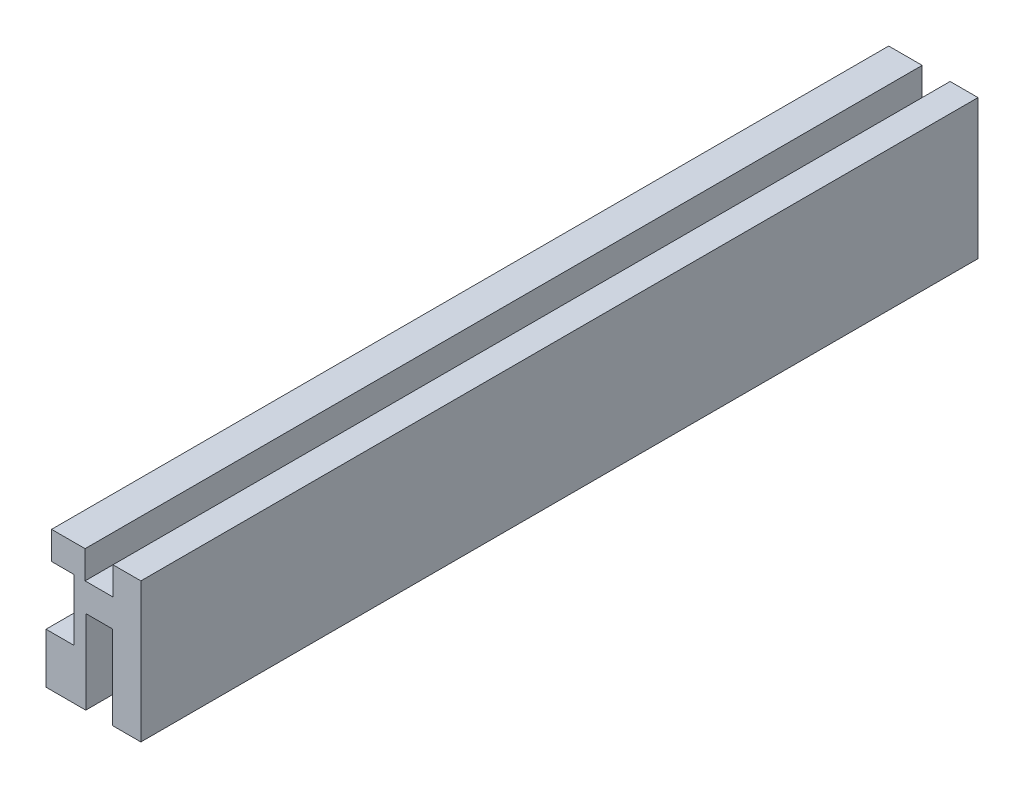
SolidWorks part; units mm, degrees
material "ABS"
ref_plane "Front Plane" through (0, 0, 0) normal (0, 0, 1) x (1, 0, 0)
ref_plane "Top Plane" through (0, 0, 0) normal (0, 1, 0) x (1, 0, 0)
ref_plane "Right Plane" through (0, 0, 0) normal (1, 0, 0) x (0, 0, -1)
sketch "Sketch1" plane through (0, 0, 0) normal (0, 0, 1) x (1, 0, 0)
  line L0 (0, 25) -> (0, -25) construction
  line L1 (15, 25) -> (5, 25)
  line L2 (-17, 25) -> (-17, 15)
  line L3 (-17, 15) -> (-9, 15)
  line L4 (-9, 15) -> (-9, -7)
  line L5 (-9, -7) -> (-19, -7)
  line L6 (-19, -7) -> (-19, -25)
  line L7 (-19, -25) -> (-4.75, -25)
  line L8 (-4.75, -25) -> (-4.75, 5)
  line L9 (-4.75, 5) -> (4.75, 5)
  line L10 (4.75, -25) -> (4.75, 5)
  line L11 (15, -25) -> (4.75, -25)
  line L17 (-5, 25) -> (-5, 15)
  line L18 (-5, 15) -> (5, 15)
  line L19 (5, 25) -> (5, 15)
  line L20 (-5, 25) -> (-17, 25)
  line L21 (15, 25) -> (15, -25)
  point P13 (0, 5)
  point P24 (0, 15)
  dimension "D1" = 50
  dimension "D2" = 17
  dimension "D3" = 10
  dimension "D4" = 8
  dimension "D5" = 10
  dimension "D6" = 18
  dimension "D7" = 30
  dimension "D8" = 4.75
  dimension "D9" = 5
  dimension "D10" = 10
  dimension "D11" = 10
extrude "Boss-Extrude1" add sketch "Sketch1" along normal blind 300
